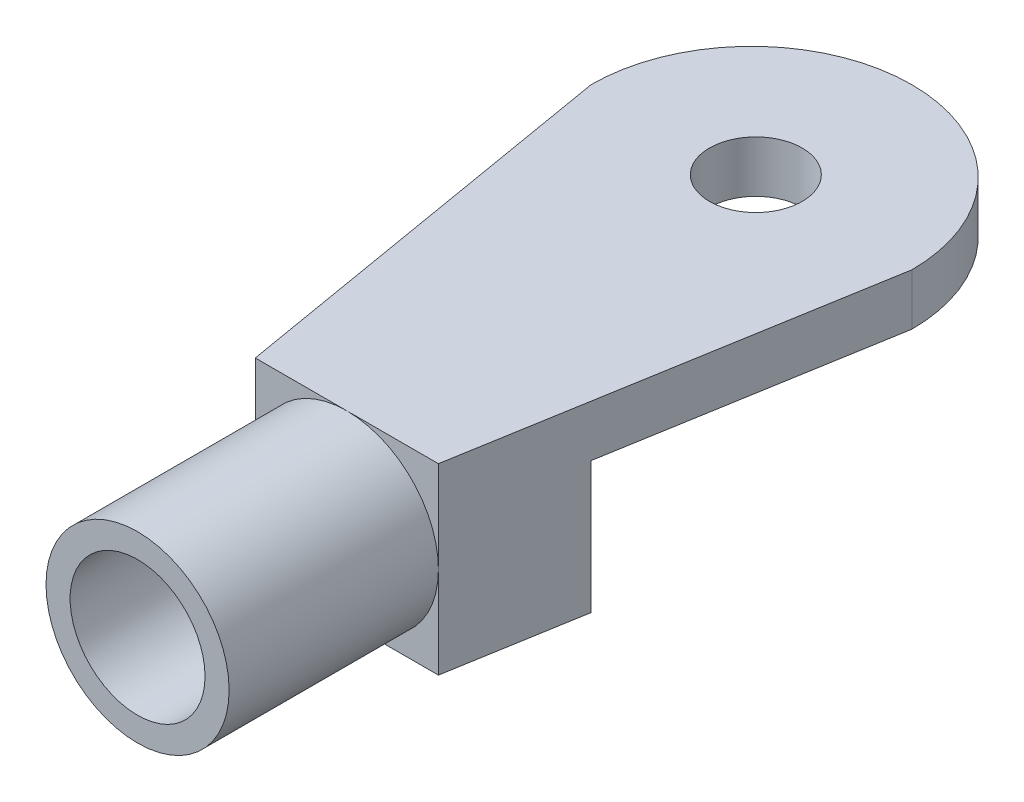
SolidWorks part; units mm, degrees
ref_plane "Front Plane" through (0, 0, 0) normal (0, 0, 1) x (1, 0, 0)
ref_plane "Top Plane" through (0, 0, 0) normal (0, 1, 0) x (1, 0, 0)
ref_plane "Right Plane" through (0, 0, 0) normal (1, 0, 0) x (0, 0, -1)
sketch "Sketch1" plane through (0, 0, 0) normal (0, 0, 1) x (1, 0, 0)
  circle A0 centre (0, 0) radius 3.275
  circle A1 centre (0, 0) radius 4.445
  dimension "D1" = 6.55
  dimension "D2" = 8.89
extrude "Boss-Extrude1" add sketch "Sketch1" along normal blind 10.16
sketch "Sketch2" plane through (0, 0, 0) normal (0, 0, -1) x (-1, 0, 0)
  line L1 (-4.445, 4.445) -> (4.445, 4.445)
  line L2 (-4.445, 4.445) -> (-4.445, -4.445)
  line L3 (-4.445, -4.445) -> (4.445, -4.445)
  line L4 (4.445, 4.445) -> (4.445, -4.445)
  circle A1 centre (0, 0) radius 4.445 construction
extrude "Boss-Extrude2" add sketch "Sketch2" along normal blind 25.4
sketch "Sketch8" plane through (0, -4.445, 0) normal (0, -1, 0) x (-1, 0, 0)
  line L0 (7.7849, 19.6415) -> (4.445, 0)
  line L1 (4.445, 0) -> (-4.445, 0)
  line L2 (-4.445, 0) -> (-7.7849, 19.6415)
  arc A0 (7.7849, 19.6415) -> (-7.7849, 19.6415) centre (0, 19.6415) ccw
  point P1 (-7.7849, 19.6415)
extrude "Boss-Extrude3" add sketch "Sketch8" against normal up to surface (8.89 mm away) up to face at (0, 4.445, -10.16)
sketch "Sketch9" plane through (0, 4.445, 0) normal (0, 1, 0) x (1, 0, 0)
  circle A0 centre (0, 19.8533) radius 2.25
  dimension "D1" = 4.5
extrude "Cut-Extrude1" cut sketch "Sketch9" against normal through all
sketch "Sketch11" plane through (0, -4.445, 0) normal (0, -1, 0) x (1, 0, 0)
  line L0 (-5.5212, -6.3291) -> (5.5212, -6.3291)
  line L4 (7.7849, -19.6415) -> (4.445, 0)
  line L5 (4.445, 0) -> (0, 0)
  line L6 (0, 0) -> (-4.445, 0)
  line L7 (-4.445, 0) -> (-7.7849, -19.6415)
  line L8 (7.7849, -19.6415) -> (4.445, 0)
  line L9 (4.445, 0) -> (0, 0)
  line L10 (0, 0) -> (-4.445, 0)
  line L11 (-4.445, 0) -> (-7.7849, -19.6415)
  arc A1 (-7.7849, -19.6415) -> (7.7849, -19.6415) centre (0, -19.6415) ccw
  arc A2 (-7.7849, -19.6415) -> (7.7849, -19.6415) centre (0, -19.6415) ccw
  circle M7 centre (0, -19.8533) radius 2.25
  line M8 (7.7849, -19.6415) -> (4.445, 0)
  line M11 (-4.445, 0) -> (-7.7849, -19.6415)
  arc M12 (-7.7849, -19.6415) -> (7.7849, -19.6415) centre (0, -19.6415) ccw
  dimension "D1" = 0
extrude "Cut-Extrude4" cut sketch "Sketch11" against normal blind 6.39 contours L0 M11 M12 M8 M7
